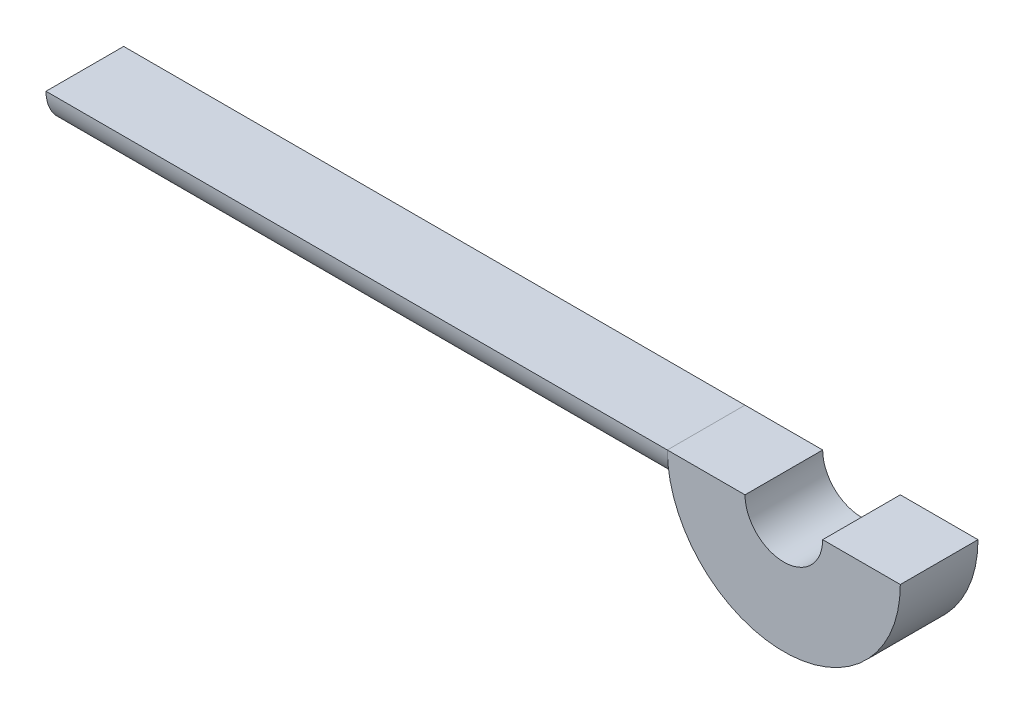
SolidWorks part; units mm, degrees
ref_plane "Front Plane" through (0, 0, 0) normal (0, 0, 1) x (1, 0, 0)
ref_plane "Top Plane" through (0, 0, 0) normal (0, 1, 0) x (1, 0, 0)
ref_plane "Right Plane" through (0, 0, 0) normal (1, 0, 0) x (0, 0, -1)
sketch "Sketch2" plane through (0, 0, 0) normal (0, 0, 1) x (1, 0, 0)
  line L0 (-9.525, 0) -> (-3.175, 0)
  line L1 (3.175, 0) -> (9.525, 0)
  arc A0 (-3.175, 0) -> (3.175, 0) centre (0, 0) ccw
  arc A1 (-9.525, 0) -> (9.525, 0) centre (0, 0) ccw
  circle A2 centre (0, 0) radius 9.525 construction
  circle A3 centre (0, 0) radius 3.175 construction
  dimension "D1" = 6.35
  dimension "D2" = 6.35
extrude "Boss-Extrude1" add sketch "Sketch2" along normal blind 6.35
ref_plane "Plane1" through (-9.525, 0, 0) normal (-1, 0, 0) x (0, 0, 1)
sketch "Sketch3" plane through (-9.525, 0, 0) normal (-1, 0, 0) x (0, 0, 1)
  line L10 (6.35, 0) -> (0, 0) construction
  line L11 (0, 0) -> (6.35, 0)
  arc A0 (0, 0) -> (6.35, 0) centre (3.175, 0) ccw
extrude "Boss-Extrude2" add sketch "Sketch3" along normal blind 50.8 and the other way up to next separate body contours A0 L11
